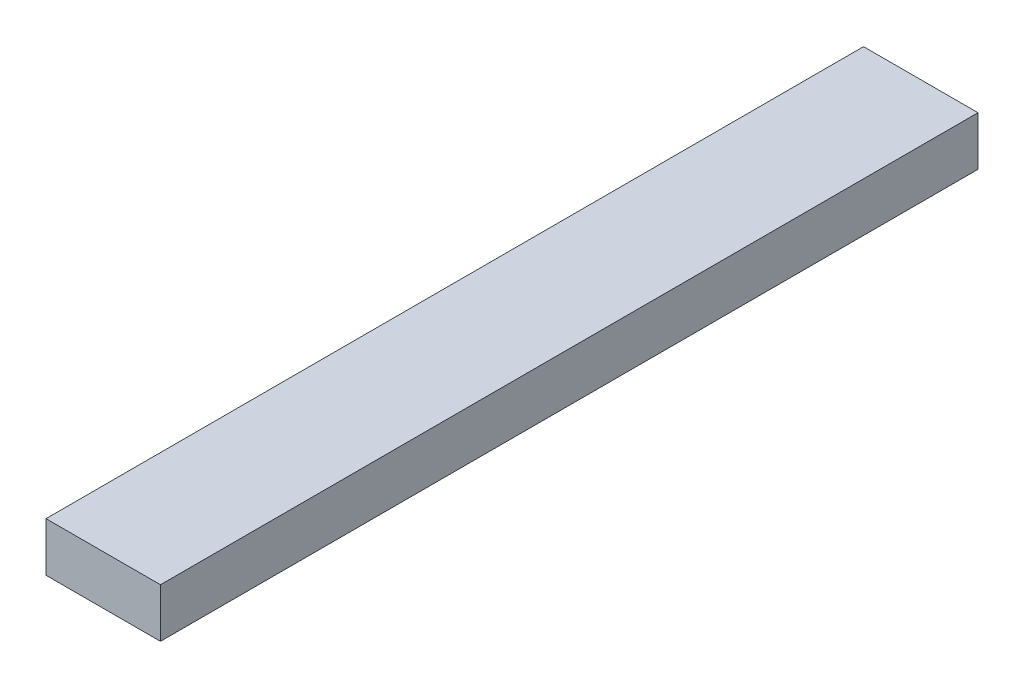
SolidWorks part; units mm, degrees
material "Pine"
ref_plane "Front Plane" through (0, 0, 0) normal (0, 0, 1) x (1, 0, 0)
ref_plane "Top Plane" through (0, 0, 0) normal (0, 1, 0) x (1, 0, 0)
ref_plane "Right Plane" through (0, 0, 0) normal (1, 0, 0) x (0, 0, -1)
sketch "Sketch1" plane through (0, 0, 0) normal (0, 0, 1) x (1, 0, 0)
  line L1 (0, 0) -> (88.9, 0)
  line L2 (0, 0) -> (0, -38.1)
  line L3 (0, -38.1) -> (88.9, -38.1)
  line L4 (88.9, 0) -> (88.9, -38.1)
  dimension "D1" = 88.9
  dimension "D2" = 38.1
extrude "Boss-Extrude1" add sketch "Sketch1" along normal blind 635
equation "\"TableFrontWidth\"=64"
equation "\"TableSideWidth\"=28"
equation "\"LegWidth\"=3.5"
equation "\"LegHeight\"=32"
equation "\"LegDistToBottomStretcher\"=7"
equation "\"BottomStretcherLength\"=\"TableFrontWidth\""
equation "\"SideStretcherLength\"=\"TableSideWidth\"-3"
equation "\"BottomSupportLength\"=\"TableSideWidth\"-3"
equation "\"D1@Boss-Extrude1\"=\"SideStretcherLength\""
equation "\"BottomPlywoodFrontDim\"=\"TableFrontWidth\"-\"LegWidth\"*2-3"
equation "\"BottomPlywoodSideDim\"=\"BottomSupportLength\""
equation "\"TotalBottomSupports\"=4"
equation "\"TotalBottomSupportsLessOne\"=\"TotalBottomSupports\"-1"
equation "\"TotalTopSupports\"=5"
equation "\"TotalTopSupportsLessOne\"=\"TotalTopSupports\"-1"
equation "\"TopSupportSpread\"=\"TableFrontWidth\"-1.5"
equation "\"DistBetweenTopSupports\"=\"TopSupportSpread\"/\"TotalTopSupportsLessOne\""
equation "\"BottomSupportSpread\"= \"BottomPlywoodFrontDim\" - 1.5"
equation "\"DistBetweenBottomSupports\"=\"BottomSupportSpread\"/\"TotalBottomSupportsLessOne\""
equation "\"OverhangFrontDim\"=4"
equation "\"OverhangSideDim\"=4"
